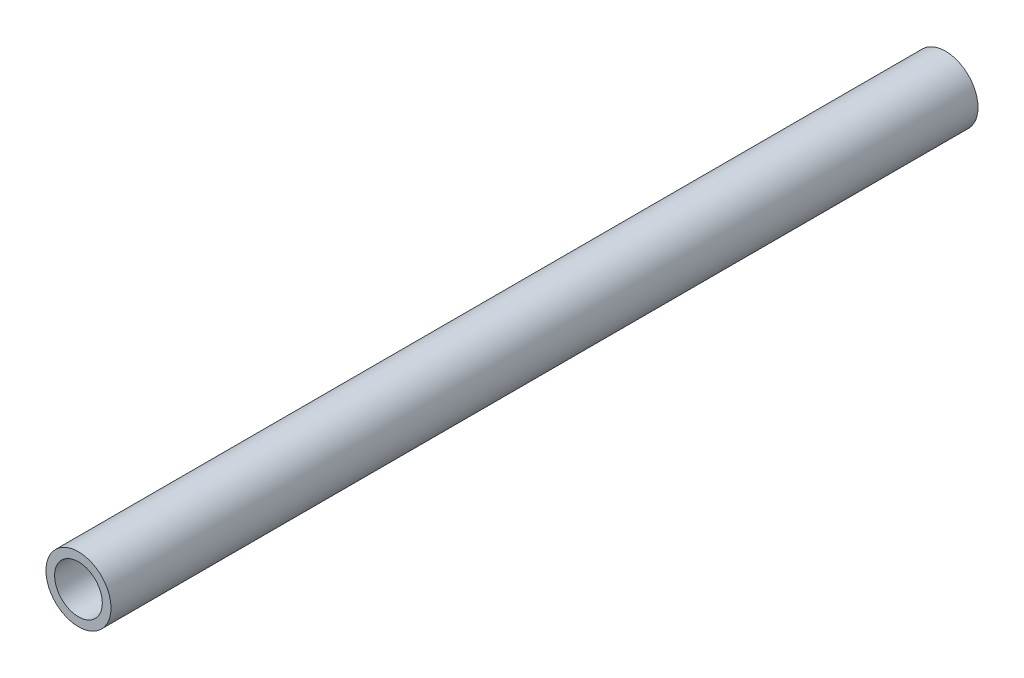
SolidWorks part; units mm, degrees
ref_plane "Front Plane" through (0, 0, 0) normal (0, 0, 1) x (1, 0, 0)
ref_plane "Top Plane" through (0, 0, 0) normal (0, 1, 0) x (1, 0, 0)
ref_plane "Right Plane" through (0, 0, 0) normal (1, 0, 0) x (0, 0, -1)
sketch "Sketch1" plane through (0, 0, 0) normal (0, 0, 1) x (1, 0, 0)
  circle A0 centre (-32.8993, 249.8477) radius 3.75
  circle A1 centre (-32.8993, 249.8477) radius 2.75
  dimension "D1" = 1
extrude "Boss-Extrude1" add sketch "Sketch1" along normal blind 100
